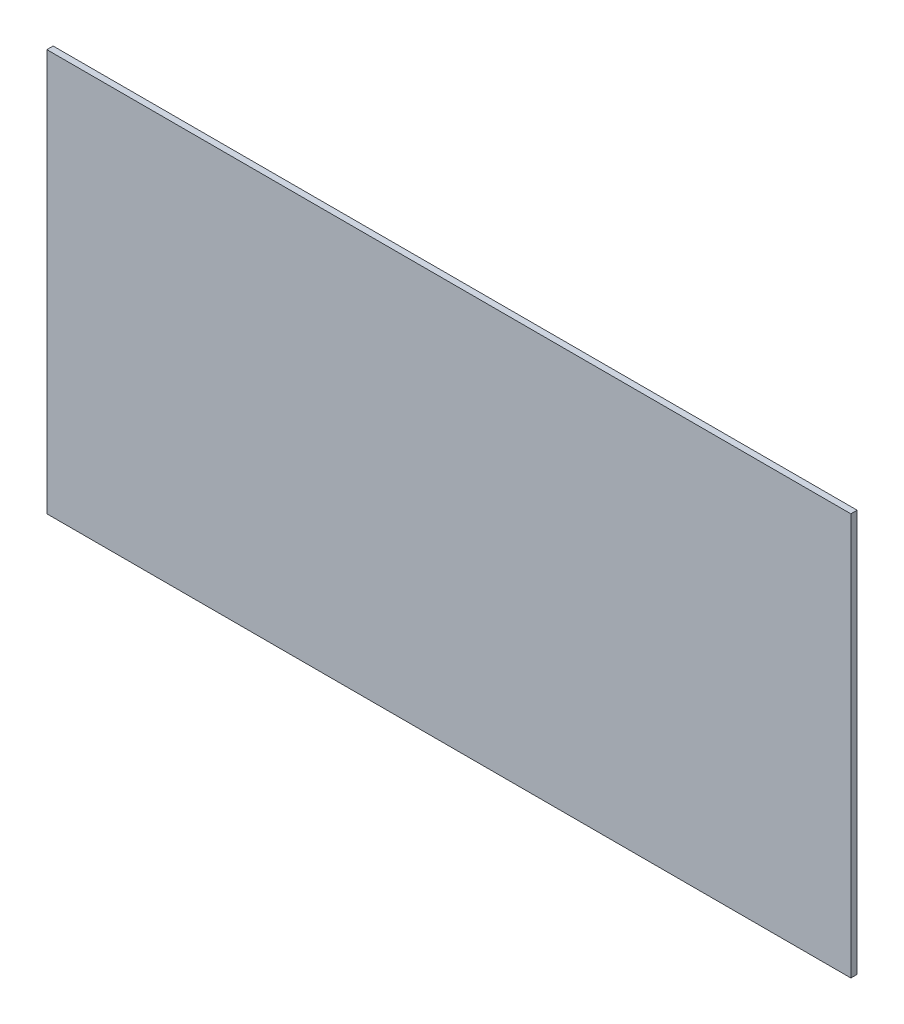
SolidWorks part; units mm, degrees
ref_plane "Front Plane" through (0, 0, 0) normal (0, 0, 1) x (1, 0, 0)
ref_plane "Top Plane" through (0, 0, 0) normal (0, 1, 0) x (1, 0, 0)
ref_plane "Right Plane" through (0, 0, 0) normal (1, 0, 0) x (0, 0, -1)
sketch "Sketch1" plane through (0, 0, 0) normal (0, 0, 1) x (1, 0, 0)
  line L1 (-304.8, -152.4) -> (304.8, -152.4)
  line L2 (-304.8, -152.4) -> (-304.8, 152.4)
  line L3 (-304.8, 152.4) -> (304.8, 152.4)
  line L4 (304.8, -152.4) -> (304.8, 152.4)
  line L5 (0, 152.4) -> (0, -152.4) construction
  line L6 (-304.8, 0) -> (304.8, 0) construction
  point P0 (0, 0)
  point P4 (-213.36, 0)
  point P5 (213.36, 0)
  point P6 (0, 106.68)
  point P7 (0, -106.68)
  dimension "Length" = 609.6
  dimension "Width" = 304.8
  dimension "Break" = 91.44
  dimension "D2" = 91.44
  dimension "D1" = 45.72
  dimension "D3" = 45.72
sketch "Sketch2" plane through (0, 0, 0) normal (1, 0, 0) x (0, 0, -1)
  line L0 (-2.3813, -152.4) -> (2.3813, -152.4)
  dimension "Thickness" = 4.7625
sketch "Sketch3" plane through (0, 0, 0) normal (0, 0, 1) x (1, 0, 0)
  line L0 (-304.8, -152.4) -> (-304.8, 152.4) construction
  line L1 (-304.8, -152.4) -> (304.8, -152.4) construction
  line L2 (304.8, -152.4) -> (304.8, 152.4) construction
  line L3 (-304.8, 152.4) -> (304.8, 152.4) construction
  line L4 (-304.8, -152.4) -> (-304.8, 152.4)
  line L5 (-304.8, -152.4) -> (304.8, -152.4)
  line L6 (304.8, -152.4) -> (304.8, 152.4)
  line L7 (-304.8, 152.4) -> (304.8, 152.4)
extrude "Boss-Extrude1" add sketch "Sketch3" along normal mid plane 4.7625
equation "\"D1@Boss-Extrude1\"=\"thickness@sketch2\""
equation "\"Break@Sketch1\" = \"Length@Sketch1\" * 0.15"
equation "\"D2@Sketch1\" = \"Break@Sketch1\""
equation "\"D1@Sketch1\"=\"Width@Sketch1\"*0.15"
equation "\"D3@Sketch1\"=\"D1@Sketch1\""
